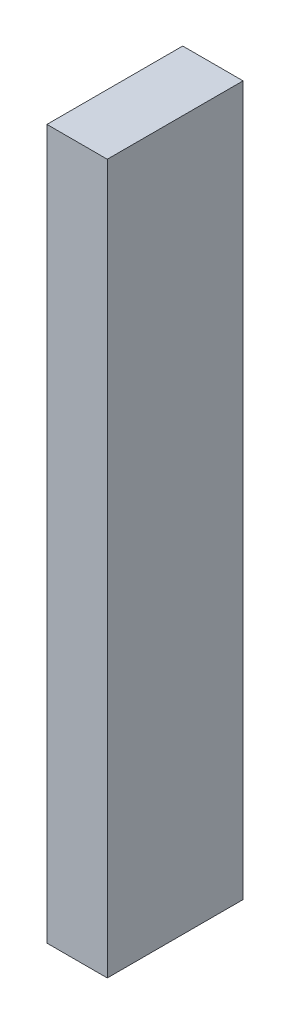
SolidWorks part; units mm, degrees
material "MDF"
ref_plane "Front Plane" through (0, 0, 0) normal (0, 0, 1) x (1, 0, 0)
ref_plane "Top Plane" through (0, 0, 0) normal (0, 1, 0) x (1, 0, 0)
ref_plane "Right Plane" through (0, 0, 0) normal (1, 0, 0) x (0, 0, -1)
sketch "Sketch1" plane through (0, 0, 0) normal (0, 0, 1) x (1, 0, 0)
  line L1 (-126.4888, -460.375) -> (-113.7888, -460.375)
  line L2 (-126.4888, -460.375) -> (-126.4888, -311.15)
  line L3 (-126.4888, -311.15) -> (-113.7888, -311.15)
  line L4 (-113.7888, -460.375) -> (-113.7888, -311.15)
  line L6 (-104.775, -463.55) -> (-126.4888, -463.55) construction
  dimension "D1" = 12.7
  dimension "D2" = 3.175
extrude "Boss-Extrude1" add sketch "Sketch1" along normal up to surface (28.575 mm away)
hole_wizard "Hole1" positions "Sketch2" profile "Sketch3" legacy
sketch "Sketch2" plane through (0, 0, -25.4) normal (0, 0, -1) x (-1, 0, 0)
  line L0 (218.5638, 0) -> (218.5638, -437.642) construction
  line L4 (104.2638, 0) -> (104.2638, -298.45) construction
  line L13 (120.1388, -463.55) -> (120.1388, -311.15) construction
  line L16 (126.4888, -311.15) -> (113.7888, -311.15) construction
  line L18 (126.4888, -304.8) -> (-126.4888, -304.8) construction
  line L22 (94.7388, -276.225) -> (-94.7388, -276.225) construction
  line L24 (-94.7388, -285.75) -> (-94.7388, -266.7) construction
  line L26 (94.7388, -285.75) -> (94.7388, -266.7) construction
  line L27 (-94.7388, 0) -> (-94.7388, -19.05) construction
  line L29 (94.7388, 0) -> (94.7388, -19.05) construction
  line L31 (94.7388, -9.525) -> (-94.7388, -9.525) construction
  point P15 (218.5638, -31.75)
  point P17 (218.5638, -218.821)
  point P19 (218.5638, -418.592)
  point P28 (104.2638, -19.05)
  point P30 (104.2638, -149.225)
  point P32 (104.2638, -279.4)
  point P69 (120.1388, -330.2)
  point P71 (120.1388, -444.5)
  point P76 (-120.1388, -444.5)
  point P77 (-120.1388, -330.2)
  point P80 (-104.2638, -279.4)
  point P81 (-104.2638, -149.225)
  point P82 (-104.2638, -19.05)
  point P83 (-218.5638, -418.592)
  point P84 (-218.5638, -218.821)
  point P85 (-218.5638, -31.75)
  point P99 (0, -304.8)
  point P101 (107.4388, -304.8)
  point P103 (-107.4388, -304.8)
  point P127 (75.6888, -276.225)
  point P129 (0, -276.225)
  point P131 (-75.6888, -276.225)
  point P152 (75.6888, -9.525)
  point P154 (0, -9.525)
  point P156 (-75.6888, -9.525)
sketch "Sketch3" plane through (75.6888, -9.525, -25.4) normal (1, 0, 0) x (0, 1, 0)
  line L0 (0, 0) -> (0, 39.0539)
  line L1 (0, 39.0539) -> (1.5875, 38.1)
  line L2 (1.5875, 38.1) -> (1.5875, 4.0177)
  line L3 (1.5875, 4.0177) -> (5.08, 0)
  line L4 (5.08, 0) -> (0, 0)
  line L5 (0, -14.3089) -> (0, 102.4216) construction
  line L6 (0, 39.0539) -> (-1.5875, 38.1) construction
  line L7 (-1.5875, 4.0177) -> (-5.08, 0) construction
  dimension "Diameter" = 3.175
  dimension "Depth" = 38.1
  dimension "C-Sink Diameter" = 10.16
  dimension "C-Sink Angle" = 82
  dimension "Drill Angle" = 118
